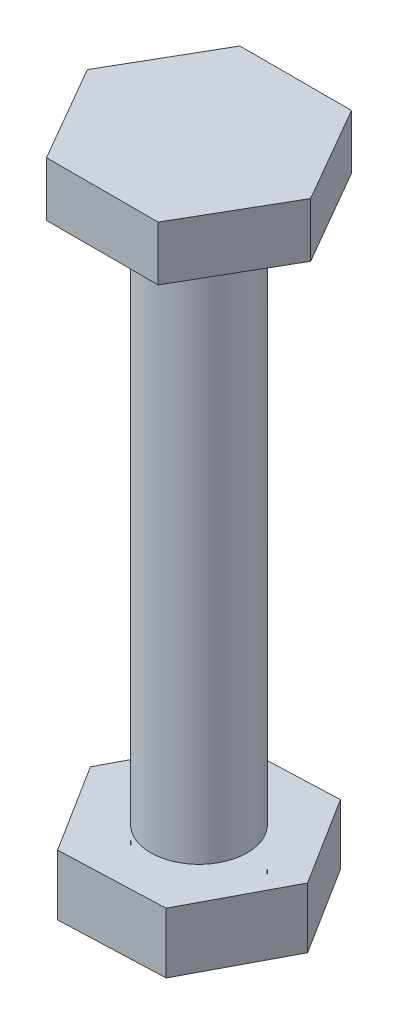
SolidWorks part; units mm, degrees
ref_plane "前视基准面" through (0, 0, 0) normal (0, 0, 1) x (1, 0, 0)
ref_plane "上视基准面" through (0, 0, 0) normal (0, 1, 0) x (1, 0, 0)
ref_plane "右视基准面" through (0, 0, 0) normal (1, 0, 0) x (0, 0, -1)
sketch "草图1" plane through (0, 0, 0) normal (0, 1, 0) x (1, 0, 0)
  line L1 (-12.8641, 0) -> (-17.4829, 8)
  line L2 (-17.4829, 8) -> (-26.7205, 8)
  line L3 (-26.7205, 8) -> (-31.3393, 0)
  line L4 (-31.3393, 0) -> (-26.7205, -8)
  line L5 (-26.7205, -8) -> (-17.4829, -8)
  line L6 (-17.4829, -8) -> (-12.8641, 0)
  circle A0 centre (-22.1017, 0) radius 8 construction
  dimension "D1" = 16
extrude "凸台-拉伸1" add sketch "草图1" along normal blind 4.5
sketch "草图2" plane through (0, 0, 0) normal (0, -1, 0) x (1, 0, 0)
  circle A0 centre (-22.1017, 0) radius 4
  dimension "D1" = 8
extrude "凸台-拉伸2" add sketch "草图2" along normal blind 50
sketch "草图3" plane through (0, -50, 0) normal (0, -1, 0) x (1, 0, 0)
  line L1 (-13.4477, -0.3303) -> (-17.4887, 7.3294)
  line L2 (-17.4887, 7.3294) -> (-26.1426, 7.6597)
  line L3 (-26.1426, 7.6597) -> (-30.7556, 0.3303)
  line L4 (-30.7556, 0.3303) -> (-26.7146, -7.3294)
  line L5 (-26.7146, -7.3294) -> (-18.0607, -7.6597)
  line L6 (-18.0607, -7.6597) -> (-13.4477, -0.3303)
  circle A0 centre (-22.1017, 0) radius 7.5 construction
  dimension "D2" = 15
  dimension "D1" = 15
extrude "凸台-拉伸3" add sketch "草图3" against normal blind 5 separate body
